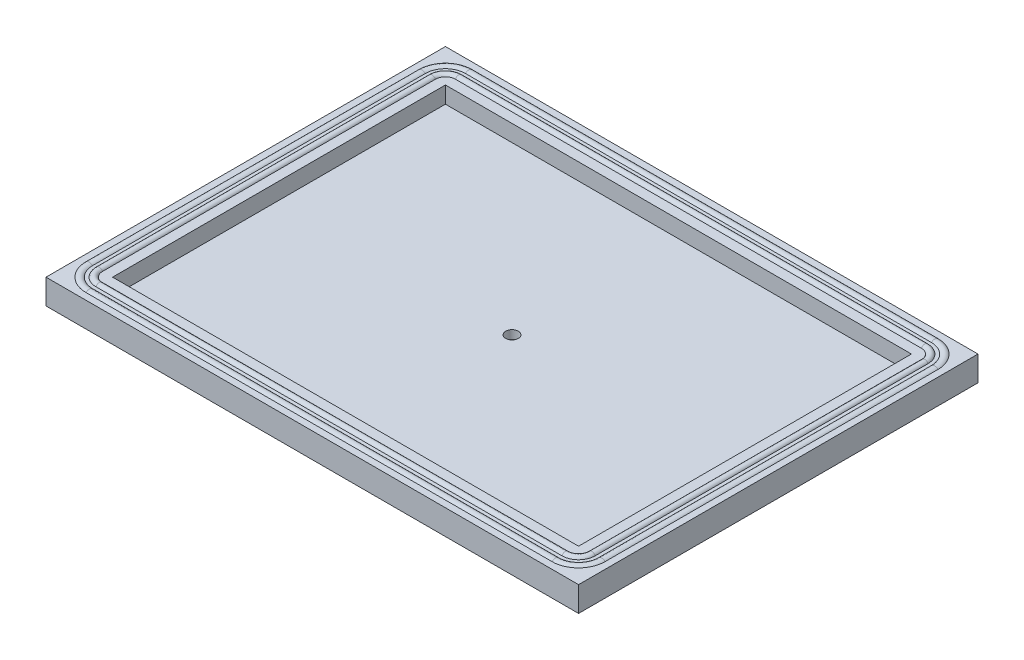
SolidWorks part; units mm, degrees
ref_plane "Front Plane" through (0, 0, 0) normal (0, 0, 1) x (1, 0, 0)
ref_plane "Top Plane" through (0, 0, 0) normal (0, 1, 0) x (1, 0, 0)
ref_plane "Right Plane" through (0, 0, 0) normal (1, 0, 0) x (0, 0, -1)
sketch "Sketch1" plane through (0, 0, 0) normal (0, 1, 0) x (1, 0, 0)
  line L12 (71.4455, 53.0596) -> (71.4455, -99.3404)
  line L13 (71.4455, -99.3404) -> (274.6455, -99.3404)
  line L14 (274.6455, -99.3404) -> (274.6455, 53.0596)
  line L15 (274.6455, 53.0596) -> (71.4455, 53.0596)
  dimension "D1" = 203.2
  dimension "D2" = 152.4
extrude "main body" add sketch "Sketch1" along normal blind 9.525
sketch "Sketch2" plane through (0, 9.525, 0) normal (0, 1, 0) x (1, 0, 0)
  line L0 (173.0455, 53.0596) -> (173.0455, 24.7212) construction
  line L1 (274.6455, 53.0596) -> (71.4455, 53.0596) construction
  line L2 (71.4455, -23.1404) -> (118.1145, -23.1404) construction
  line L3 (71.4455, 53.0596) -> (71.4455, -99.3404) construction
  line L4 (261.9455, -86.6404) -> (84.1455, -86.6404)
  line L5 (84.1455, -86.6404) -> (84.1455, 40.3596)
  line L6 (261.9455, -86.6404) -> (261.9455, 40.3596)
  line L7 (261.9455, 40.3596) -> (84.1455, 40.3596)
  line L8 (84.1455, 40.3596) -> (261.9455, -86.6404) construction
  line L9 (274.6455, -99.3404) -> (274.6455, 53.0596) construction
  line L10 (71.4455, -99.3404) -> (274.6455, -99.3404) construction
  point P11 (173.0455, 40.3596)
  point P13 (173.0455, -86.6404)
  point P14 (261.9455, -23.1404)
  point P15 (84.1455, -23.1404)
  dimension "D1" = 12.7
  dimension "D2" = 12.7
extrude "slide inset" cut sketch "Sketch2" against normal offset from surface (6.35 mm away) 3.175 up to face at (173.0455, 0, 23.1404)
sketch "offset rounded from slide" plane through (0, 9.525, 0) normal (0, 1, 0) x (1, 0, 0)
  line L8 (264.4855, -89.1804) -> (264.4855, 42.8996)
  line L9 (81.6055, -89.1804) -> (264.4855, -89.1804)
  line L10 (81.6055, 42.8996) -> (81.6055, -89.1804)
  line L11 (264.4855, 42.8996) -> (81.6055, 42.8996)
  line L12 (264.4855, -86.6404) -> (264.4855, 40.3596)
  line L13 (84.1455, -89.1804) -> (261.9455, -89.1804)
  line L14 (81.6055, 40.3596) -> (81.6055, -86.6404)
  line L15 (261.9455, 42.8996) -> (84.1455, 42.8996)
  arc A0 (84.1455, -89.1804) -> (81.6055, -86.6404) centre (84.1455, -86.6404) cw
  arc A1 (264.4855, -86.6404) -> (261.9455, -89.1804) centre (261.9455, -86.6404) cw
  arc A2 (264.4855, 40.3596) -> (261.9455, 42.8996) centre (261.9455, 40.3596) ccw
  arc A3 (81.6055, 40.3596) -> (84.1455, 42.8996) centre (84.1455, 40.3596) cw
  dimension "D2" = 2.54
  dimension "D1" = 2.54
sketch "gasket bump profiles" plane through (0, 9.525, 0) normal (0, 1, 0) x (1, 0, 0)
  line L8 (79.0655, 40.3596) -> (79.0655, -86.6404)
  line L9 (84.1455, -91.7204) -> (261.9455, -91.7204)
  line L10 (267.0255, -86.6404) -> (267.0255, 40.3596)
  line L11 (261.9455, 45.4396) -> (84.1455, 45.4396)
  line L12 (79.0655, 40.3596) -> (79.0655, -86.6404)
  line L13 (84.1455, -91.7204) -> (261.9455, -91.7204)
  line L14 (267.0255, -86.6404) -> (267.0255, 40.3596)
  line L15 (261.9455, 45.4396) -> (84.1455, 45.4396)
  arc A8 (79.0655, -86.6404) -> (84.1455, -91.7204) centre (84.1455, -86.6404) ccw
  arc A9 (261.9455, -91.7204) -> (267.0255, -86.6404) centre (261.9455, -86.6404) ccw
  arc A10 (267.0255, 40.3596) -> (261.9455, 45.4396) centre (261.9455, 40.3596) ccw
  arc A11 (84.1455, 45.4396) -> (79.0655, 40.3596) centre (84.1455, 40.3596) ccw
  arc A16 (79.0655, -86.6404) -> (84.1455, -91.7204) centre (84.1455, -86.6404) ccw
  arc A17 (261.9455, -91.7204) -> (267.0255, -86.6404) centre (261.9455, -86.6404) ccw
  arc A18 (267.0255, 40.3596) -> (261.9455, 45.4396) centre (261.9455, 40.3596) ccw
  arc A19 (84.1455, 45.4396) -> (79.0655, 40.3596) centre (84.1455, 40.3596) ccw
  dimension "D1" = 2.54
ref_plane "Plane1 for gasket bump shape" through (0, 0, 23.1404) normal (0, 0, -1) x (-1, 0, 0)
sketch "gasket bump shape" plane through (0, 0, 23.1404) normal (0, 0, -1) x (-1, 0, 0)
  line L0 (-79.0655, 9.525) -> (-79.0655, 13.8205) construction
  line L1 (-77.7955, 9.525) -> (-80.3355, 9.525)
  line L2 (-79.0655, 10.3187) -> (-89.9155, 10.3187) construction
  line L3 (-79.0655, 9.525) -> (-75.2555, 9.525) construction
  line L4 (-77.1605, 9.525) -> (-77.1605, 13.8205) construction
  line L5 (-76.5255, 9.525) -> (-73.9855, 9.525)
  line L6 (-75.2555, 10.033) -> (-81.1283, 10.033) construction
  line L8 (-274.6455, 9.525) -> (-71.4455, 9.525) construction
  arc A0 (-77.7955, 9.525) -> (-80.3355, 9.525) centre (-79.0655, 8.9059) ccw
  arc A1 (-76.5255, 9.525) -> (-73.9855, 9.525) centre (-75.2555, 8.1915) cw
  dimension "D1" = 0.7937
  dimension "D2" = 2.54
  dimension "D3" = 3.81
  dimension "D4" = 0.508
sweep "Sweep for sealing ribs" add profiles "gasket bump shape" path "gasket bump profiles"
hole_wizard "#10-32 Tapped Hole2" positions "Sketch26" profile "Sketch27" tap size "#10-32" standard "ANSI Inch" end condition through all
sketch "Sketch26" plane through (0, 0, 0) normal (0, -1, 0) x (1, 0, 0)
  line L0 (71.4455, 99.3404) -> (274.6455, 99.3404) construction
  line L1 (71.4455, -53.0596) -> (71.4455, 99.3404) construction
  point P0 (173.0455, 23.1404)
  point P4 (173.0455, 99.3404)
  point P7 (71.4455, 23.1404)
sketch "Sketch27" plane through (173.0455, 0, 23.1404) normal (1, 0, 0) x (0, 0, -1)
  line L0 (0, 0) -> (0, 10.3187)
  line L1 (0, 10.3187) -> (2.413, 10.3187)
  line L2 (2.413, 10.3187) -> (2.413, 0)
  line L5 (2.413, 0) -> (0, 0)
  line L11 (0, -6.35) -> (0, 107.95) construction
  dimension "Thread Major Dia." = 4.826
  dimension "Thru Tap Drill Depth" = 10.3187
equation "\"BodyLength\"=8"
equation "\"BodyWidth\"=6"
equation "\"D2@Sketch1\"=\"BodyWidth\""
equation "\"D1@Sketch1\"= \"BodyLength\""
equation "\"SealingEdge\"=0.5"
equation "\"D1@Sketch2\"=\"SealingEdge\""
equation "\"D2@Sketch2\"=\"SealingEdge\""
equation "\"ShellHeight\"=0.375"
equation "\"D1@main body\"=\"ShellHeight\""
